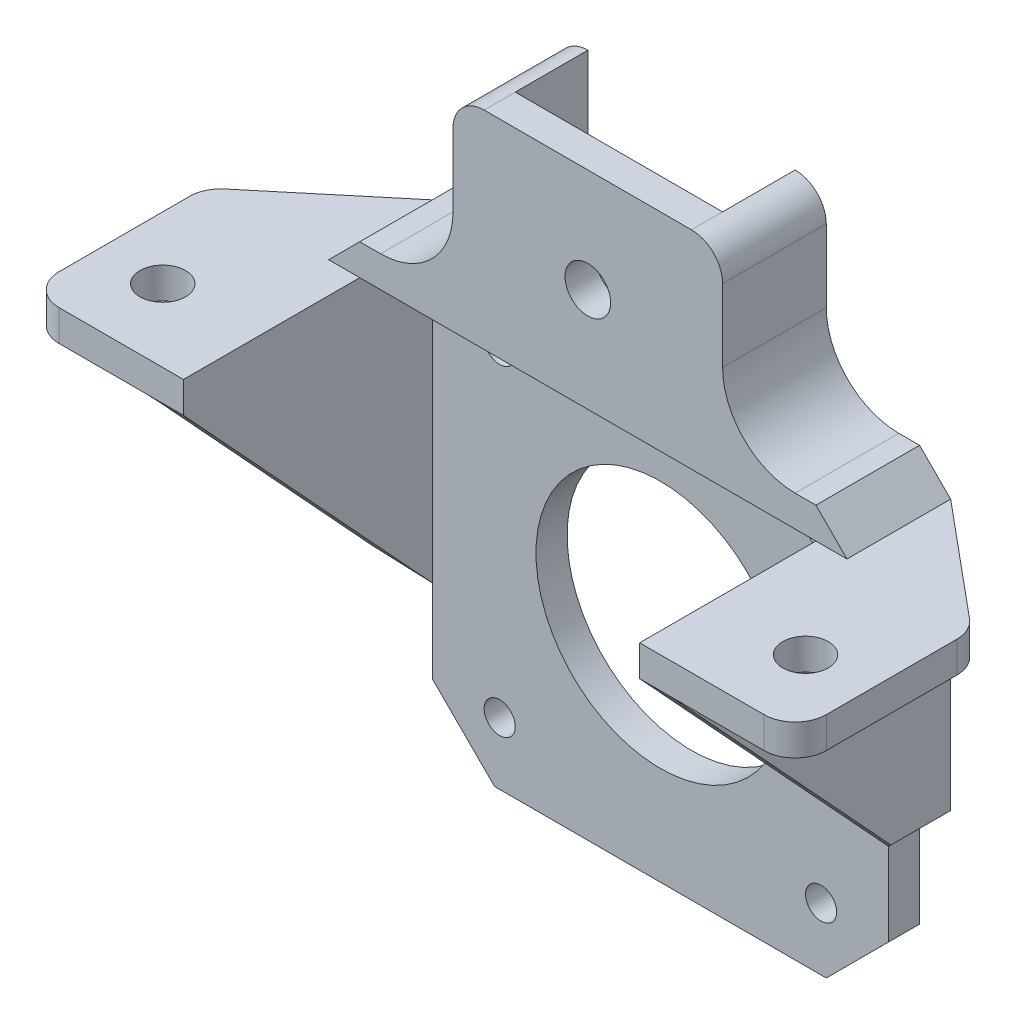
SolidWorks part; units mm, degrees
material "ABS"
ref_plane "Front Plane" through (0, 0, 0) normal (0, 0, 1) x (1, 0, 0)
ref_plane "Top Plane" through (0, 0, 0) normal (0, 1, 0) x (1, 0, 0)
ref_plane "Right Plane" through (0, 0, 0) normal (1, 0, 0) x (0, 0, -1)
sketch "Sketch1" plane through (0, 0, 0) normal (0, 0, 1) x (1, 0, 0)
  line L0 (-13, 21.5) -> (-13, 41.5)
  line L1 (-22, -21.5) -> (22, -21.5)
  line L2 (-22, -21.5) -> (-22, 21.5)
  line L3 (-22, 21.5) -> (-13, 21.5)
  line L4 (22, -21.5) -> (22, 21.5)
  line L5 (-22, -21.5) -> (22, 21.5) construction
  line L6 (-22, 21.5) -> (22, -21.5) construction
  line L7 (-13, 41.5) -> (13, 41.5)
  line L8 (13, 41.5) -> (13, 21.5)
  line L9 (13, 21.5) -> (22, 21.5)
  point P0 (0, 0)
  dimension "D1" = 44
  dimension "D2" = 43
  dimension "D3" = 20
  dimension "D4" = 26
extrude "Boss-Extrude1" add sketch "Sketch1" along normal blind 3
sketch "Sketch2" plane through (0, 0, 0) normal (0, 0, -1) x (-1, 0, 0)
  line L0 (37, 21.5) -> (22, 21.5)
  line L1 (22, 21.5) -> (22, -7.5)
  line L2 (22, -7.5) -> (25, -7.5)
  line L3 (25, -7.5) -> (25, 18.5)
  line L4 (25, 18.5) -> (37, 18.5)
  line L5 (37, 18.5) -> (37, 21.5)
  line L7 (22, -21.5) -> (-22, -21.5) construction
  line L8 (0, -21.5) -> (0, -14.1694) construction
  line L9 (-37, 18.5) -> (-37, 21.5)
  line L10 (-25, 18.5) -> (-37, 18.5)
  line L11 (-25, -7.5) -> (-25, 18.5)
  line L12 (-22, -7.5) -> (-25, -7.5)
  line L13 (-22, 21.5) -> (-22, -7.5)
  line L14 (-37, 21.5) -> (-22, 21.5)
  line L15 (22, 21.5) -> (22, -21.5) construction
  dimension "D1" = 3
  dimension "D2" = 3
  dimension "D4" = 14
  dimension "D5" = 29
  dimension "D6" = 15
extrude "Boss-Extrude2" add sketch "Sketch2" against normal blind 27 separate body
sketch "Sketch3" plane through (0, 0, 0) normal (0, 0, -1) x (-1, 0, 0)
  line L0 (-25, 21.5) -> (-22, 24.5)
  line L1 (-22, 21.5) -> (-37, 21.5) construction
  line L2 (-22, 24.5) -> (22, 24.5)
  line L4 (22, 24.5) -> (25, 21.5)
  line L5 (37, 21.5) -> (22, 21.5) construction
  line L6 (25, 21.5) -> (-25, 21.5)
  line L8 (0, 24.5) -> (0, 41.5) construction
  line L9 (-13, 41.5) -> (13, 41.5) construction
  dimension "D1" = 3
  dimension "D2" = 44
  dimension "D3" = 50
extrude "Boss-Extrude3" add sketch "Sketch3" against normal blind 10
sketch "Sketch4" plane through (0, 0, 3) normal (0, 0, 1) x (1, 0, 0)
  line L0 (13, 24.5) -> (-13, 24.5) construction
  line L1 (-13, 41.5) -> (-13, 24.5) construction
  line L2 (-13, 24.5) -> (-13, 41.5)
  line L3 (-13, 41.5) -> (13, 41.5)
  line L4 (13, 41.5) -> (13, 24.5)
  line L5 (13, 24.5) -> (13, 41.5) construction
  line L6 (-13, 24.5) -> (13, 24.5)
extrude "Boss-Extrude4" add sketch "Sketch4" along normal up to surface (7 mm away) up to face at (0, 22.5, 10)
sketch "Sketch5" plane through (25, 0, 0) normal (1, 0, 0) x (0, 0, -1)
  line L0 (-27, 18.5) -> (-3, -7.5)
  line L1 (-3, -7.5) -> (-27, -7.5)
  line L2 (-27, -7.5) -> (-27, 18.5)
extrude "Cut-Extrude1" cut sketch "Sketch5" against normal through all
sketch "Sketch6" plane through (0, 18.5, 0) normal (0, -1, 0) x (1, 0, 0)
  line L0 (22, 10) -> (-22, 10) construction
  line L2 (37, 27) -> (37, 0) construction
  line L4 (25, 0) -> (37, 10)
  line L5 (37, 10) -> (37, 0)
  line L6 (37, 0) -> (25, 0)
  line L7 (25, 27) -> (22, 27) construction
  line L8 (0, 10) -> (0, 24.5) construction
  line L10 (-37, 0) -> (-25, 0)
  line L11 (-37, 10) -> (-37, 0)
  line L12 (-25, 0) -> (-37, 10)
  circle A0 centre (31, 20) radius 2.2
  circle A1 centre (-31, 20) radius 2.2
  dimension "D3" = 4.4
  dimension "D4" = 6
  dimension "D5" = 7
  dimension "D1" = 10
extrude "Cut-Extrude2" cut sketch "Sketch6" against normal through all
sketch "Sketch7" plane through (0, 41.5, 0) normal (0, 1, 0) x (1, 0, 0)
  line L0 (13, 0) -> (-13, 0) construction
  line L1 (-10, 0) -> (10, 0)
  line L2 (-10, 0) -> (-10, -7)
  line L3 (-10, -7) -> (10, -7)
  line L4 (10, 0) -> (10, -7)
  line L5 (13, -10) -> (13, 0) construction
  line L6 (-13, -10) -> (-13, 0) construction
  line L7 (13, -10) -> (-13, -10) construction
  dimension "D1" = 3
  dimension "D2" = 3
  dimension "D3" = 3
extrude "Cut-Extrude3" cut sketch "Sketch7" against normal blind 17
sketch "Sketch8" plane through (0, 0, 3) normal (0, 0, 1) x (1, 0, 0)
  line L0 (-15.5, 15.5) -> (15.5, 15.5) construction
  line L1 (15.5, 15.5) -> (15.5, -15.5) construction
  line L2 (15.5, -15.5) -> (-15.5, 15.5) construction
  line L3 (-22, -21.5) -> (22, -21.5) construction
  line L4 (0, 0) -> (0, -21.5) construction
  circle A0 centre (0, 0) radius 12
  circle A1 centre (-15.5, 15.5) radius 1.5
  circle A2 centre (15.5, 15.5) radius 1.5
  circle A3 centre (15.5, -15.5) radius 1.5
  circle A4 centre (-15.5, -15.5) radius 1.5
  dimension "D1" = 3
  dimension "D3" = 24
  dimension "D4" = 21.5
  dimension "D2" = 31
extrude "Cut-Extrude4" cut sketch "Sketch8" against normal through all
sketch "Sketch9" plane through (0, 0, 10) normal (0, 0, 1) x (1, 0, 0)
  line L0 (13, 41.5) -> (-13, 41.5) construction
  line L1 (0, 41.5) -> (0, 31.5) construction
  circle A0 centre (0, 31.5) radius 2.2
  dimension "D1" = 4.4
  dimension "D2" = 10
extrude "Cut-Extrude5" cut sketch "Sketch9" against normal through all
fillet "Fillet1" radius 7 2 edges at (-13, 24.5, 5) (13, 24.5, 5)
fillet "Fillet2" radius 3 6 edges at (13, 41.5, 5) (-13, 41.5, 5) (-37, 20, 10) (37, 20, 10) (-37, 20, 27) (37, 20, 27)
chamfer "Chamfer1" distance 6 angle 45 2 edges at (-22, -21.5, 1.5) (22, -21.5, 1.5)
sketch "Sketch10" plane through (0, 0, 3) normal (0, 0, 1) x (1, 0, 0)
  line L0 (22, -7.5) -> (25, -4.51)
  line L1 (25, -7.5) -> (25, 18.5) construction
  line L2 (25, -4.51) -> (22.01, -7.5) construction
  line L3 (25, -4.51) -> (25, -7.5)
  line L4 (25, -7.5) -> (22, -7.5)
  line L5 (-22, -7.5) -> (-25, -7.5)
  line L6 (-22, -7.5) -> (-25, -4.51)
  line L7 (-25, 18.5) -> (-25, -7.5) construction
  line L8 (-22, -7.5) -> (-25, -4.51) construction
  line L9 (-25, -4.51) -> (-25, -7.5)
extrude "Cut-Extrude6" cut sketch "Sketch10" against normal through all both and the other way through all
fillet "Fillet3" radius 1 2 edges at (25, 18.5, 13.5) (-25, 18.5, 13.5)
